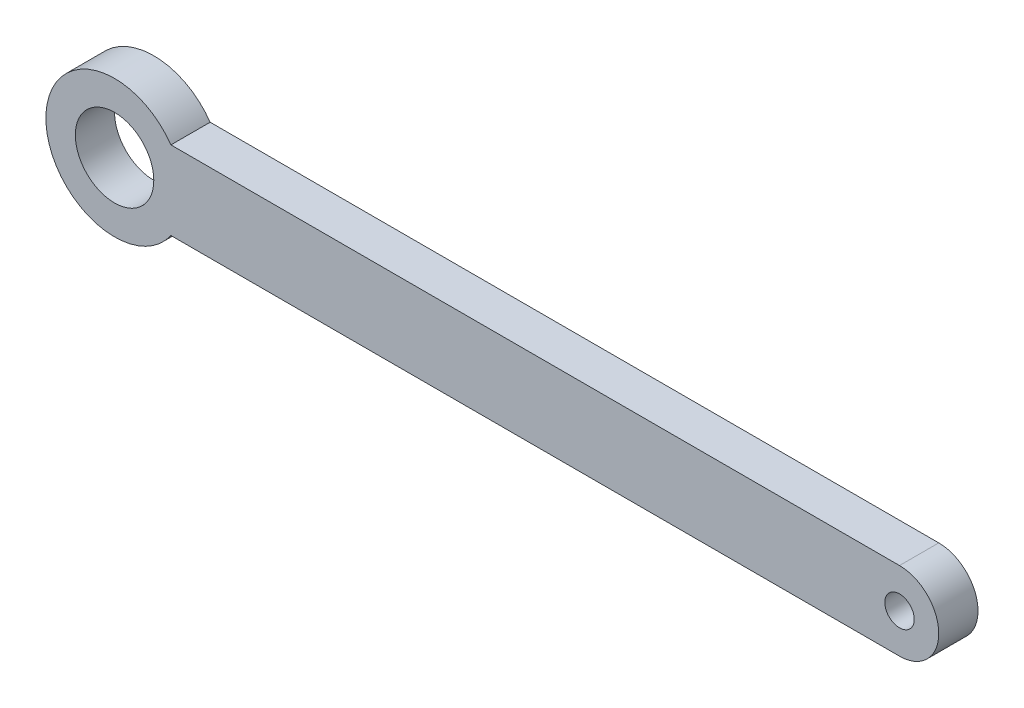
SolidWorks part; units mm, degrees
ref_plane "Front Plane" through (0, 0, 0) normal (0, 0, 1) x (1, 0, 0)
ref_plane "Top Plane" through (0, 0, 0) normal (0, 1, 0) x (1, 0, 0)
ref_plane "Right Plane" through (0, 0, 0) normal (1, 0, 0) x (0, 0, -1)
sketch "Sketch1" plane through (0, 0, 0) normal (0, 0, 1) x (1, 0, 0)
  line L0 (0, -2) -> (40, -2)
  line L1 (0, 2) -> (40, 2)
  arc A0 (0, 2) -> (0, -2) centre (0, 0) ccw
  arc A1 (40, -2) -> (40, 2) centre (40, 0) ccw
  dimension "D2" = 4
  dimension "D3" = 4
  dimension "D1" = 40
extrude "Boss-Extrude1" add sketch "Sketch1" along normal blind 2
sketch "Sketch2" plane through (0, 0, 2) normal (0, 0, 1) x (1, 0, 0)
  circle A0 centre (0, 0) radius 2
  dimension "D1" = 4
extrude "Boss-Extrude2" add sketch "Sketch2" along normal blind 8
sketch "Croquis1" plane through (0, 0, 2) normal (0, 0, 1) x (1, 0, 0)
  circle A0 centre (40, 0) radius 0.75
  dimension "D1" = 1.5
extrude "Cortar-Extruir1" cut sketch "Croquis1" against normal blind 10
sketch "Croquis2" plane through (0, 0, 10) normal (0, 0, 1) x (1, 0, 0)
  circle A0 centre (0, 0) radius 2
extrude "Cortar-Extruir2" cut sketch "Croquis2" against normal blind 16
sketch "Croquis3" plane through (0, 0, 2) normal (0, 0, 1) x (1, 0, 0)
  circle A0 centre (0, 0) radius 2
  circle A1 centre (0, 0) radius 3.5
  dimension "D1" = 1.5
extrude "Saliente-Extruir1" add sketch "Croquis3" against normal up to surface (2 mm away) up to face at (40.75, 0, 0)
